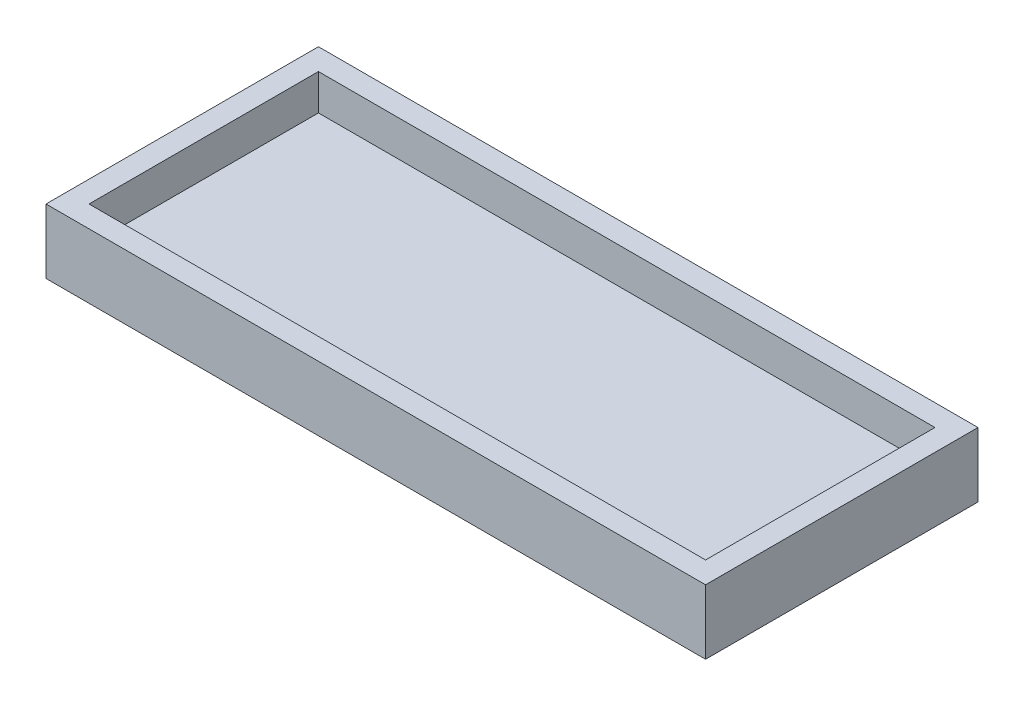
SolidWorks part; units mm, degrees
ref_plane "Front Plane" through (0, 0, 0) normal (0, 0, 1) x (1, 0, 0)
ref_plane "Top Plane" through (0, 0, 0) normal (0, 1, 0) x (1, 0, 0)
ref_plane "Right Plane" through (0, 0, 0) normal (1, 0, 0) x (0, 0, -1)
sketch "Sketch1" plane through (0, 0, 0) normal (0, 1, 0) x (1, 0, 0)
  line L1 (-21.5, 8) -> (21.5, 8)
  line L2 (-21.5, 8) -> (-21.5, -8)
  line L3 (-21.5, -8) -> (21.5, -8)
  line L4 (21.5, 8) -> (21.5, -8)
  line L5 (-21.5, 8) -> (21.5, -8) construction
  line L6 (-21.5, -8) -> (21.5, 8) construction
  point P0 (0, 0)
extrude "Boss-Extrude1" add sketch "Sketch1" along normal blind 2
sketch "Sketch2" plane through (0, 0, 0) normal (0, -1, 0) x (1, 0, 0)
  line L4 (23, -9.5) -> (23, 9.5)
  line L5 (23, 9.5) -> (-23, 9.5)
  line L6 (-23, 9.5) -> (-23, -9.5)
  line L7 (-23, -9.5) -> (23, -9.5)
  line L8 (21.5, -8) -> (21.5, 8)
  line L9 (21.5, 8) -> (-21.5, 8)
  line L10 (-21.5, 8) -> (-21.5, -8)
  line L11 (-21.5, -8) -> (21.5, -8)
  line L12 (21.5, -8) -> (21.5, 8)
  line L13 (21.5, 8) -> (-21.5, 8)
  line L14 (-21.5, 8) -> (-21.5, -8)
  line L15 (-21.5, -8) -> (21.5, -8)
  dimension "D1" = 0
  dimension "D2" = 1.5
extrude "Boss-Extrude4" add sketch "Sketch2" against normal blind 4.5
